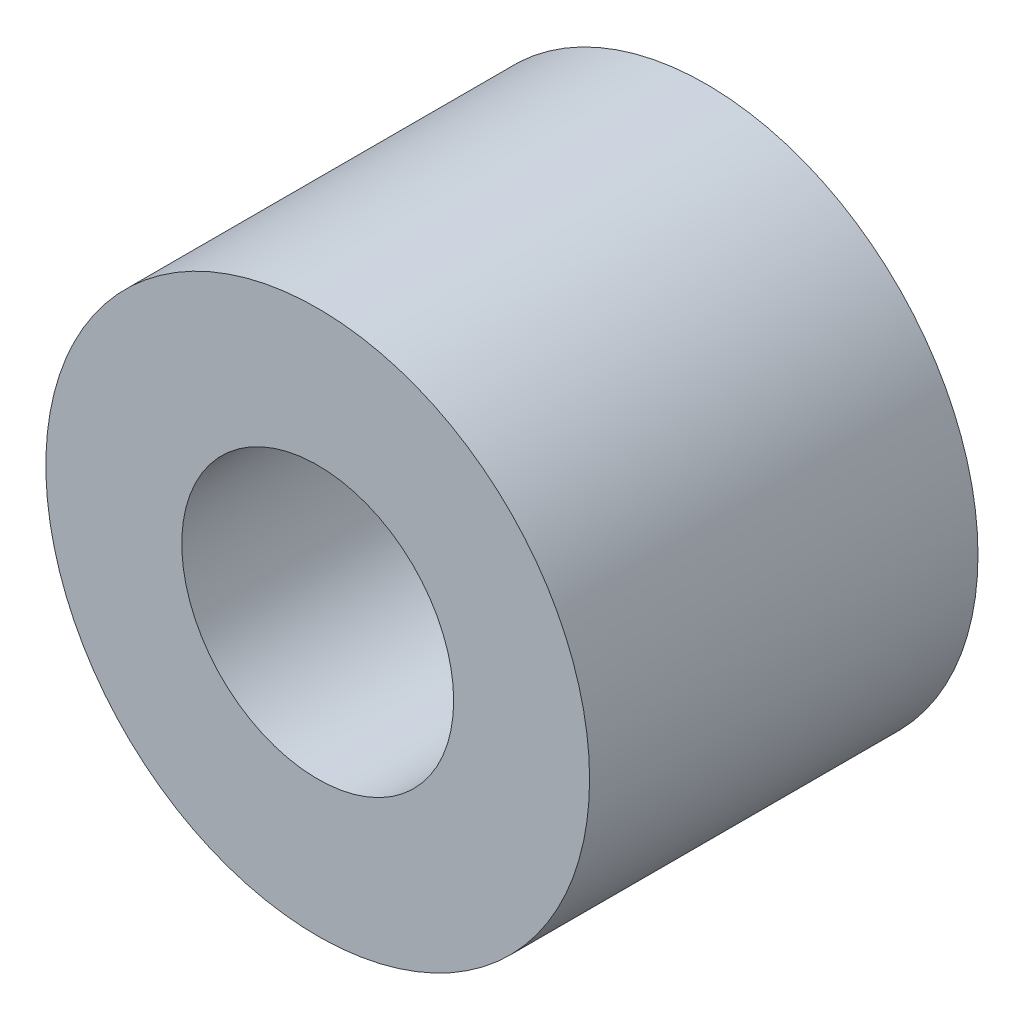
SolidWorks part; units mm, degrees
ref_plane "Front Plane" through (0, 0, 0) normal (0, 0, 1) x (1, 0, 0)
ref_plane "Top Plane" through (0, 0, 0) normal (0, 1, 0) x (1, 0, 0)
ref_plane "Right Plane" through (0, 0, 0) normal (1, 0, 0) x (0, 0, -1)
sketch "Sketch1" plane through (0, 0, 0) normal (0, 0, 1) x (1, 0, 0)
  circle A0 centre (0, 0) radius 1.75
  circle A1 centre (0, 0) radius 3.5
  dimension "D1" = 3.5
  dimension "D2" = 7
extrude "Boss-Extrude1" add sketch "Sketch1" along normal mid plane 5
